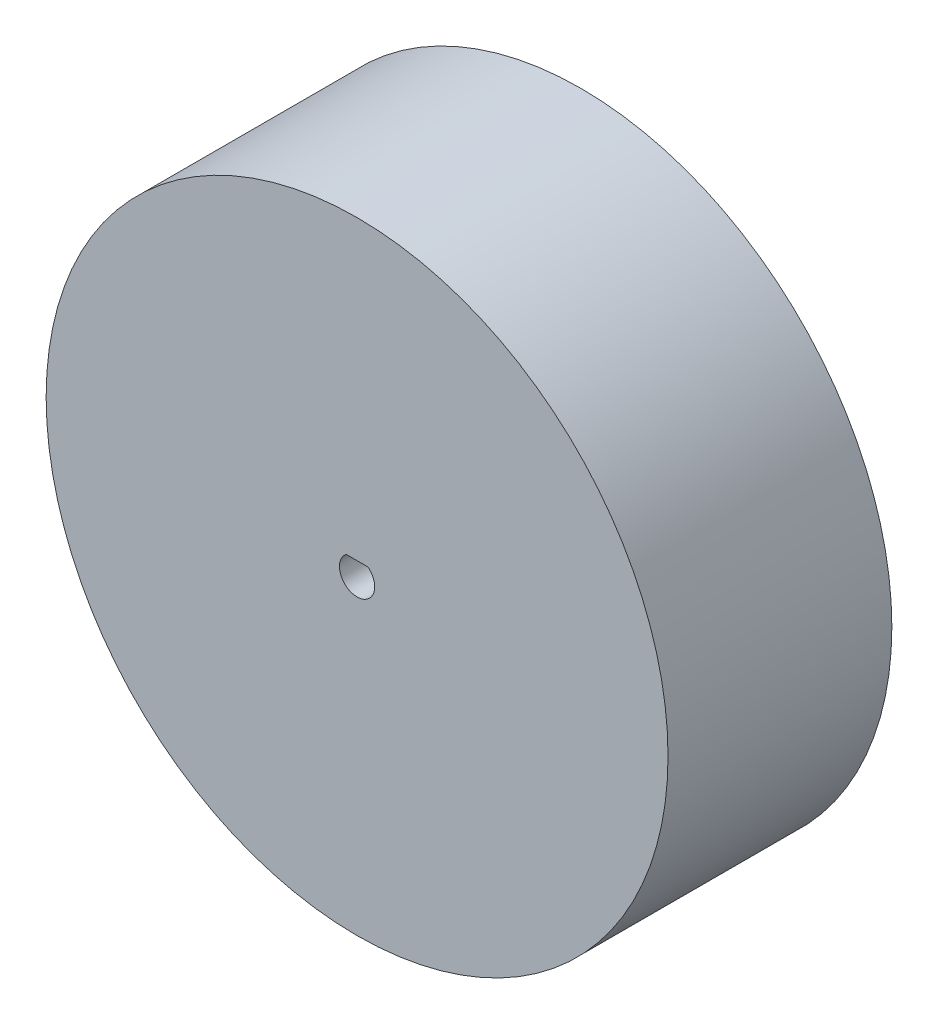
SolidWorks part; units mm, degrees
ref_plane "Front Plane" through (0, 0, 0) normal (0, 0, 1) x (1, 0, 0)
ref_plane "Top Plane" through (0, 0, 0) normal (0, 1, 0) x (1, 0, 0)
ref_plane "Right Plane" through (0, 0, 0) normal (1, 0, 0) x (0, 0, -1)
sketch "Sketch1" plane through (0, 0, 0) normal (0, 0, 1) x (1, 0, 0)
  line L0 (-1.27, 1.6025) -> (1.27, 1.6025)
  circle A0 centre (0, 0) radius 28.5
  arc A1 (-1.27, 1.6025) -> (1.27, 1.6025) centre (0, 0) ccw
  dimension "D1" = 4.0894
  dimension "D3" = 57
  dimension "D2" = 2.54
extrude "Boss-Extrude1" add sketch "Sketch1" along normal blind 26
sketch "Sketch2" plane through (0, 0, 26) normal (0, 0, 1) x (1, 0, 0)
  circle A2 centre (0, 0) radius 36.12
  circle A3 centre (0, 0) radius 36.12
  circle A4 centre (0, 0) radius 28.5
  circle A5 centre (0, 0) radius 28.5
  dimension "D1" = 7.62
  dimension "D2" = 0
extrude "Boss-Extrude2" add sketch "Sketch2" against normal up to surface (26 mm away) up to face at (28.5, 0, 0)
